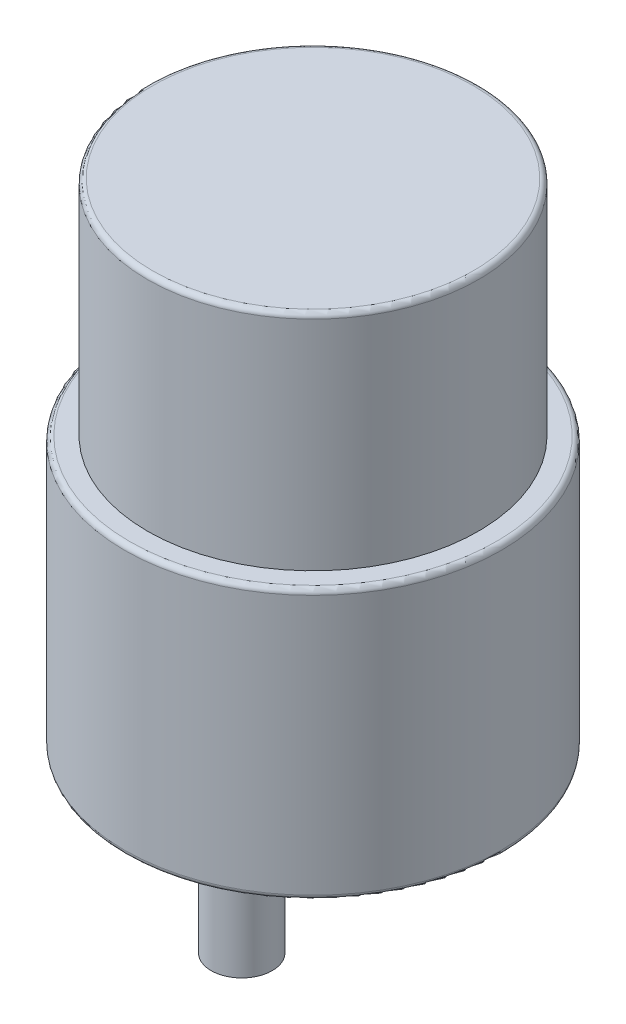
SolidWorks part; units mm, degrees
ref_plane "前视基准面" through (0, 0, 0) normal (0, 0, 1) x (1, 0, 0)
ref_plane "上视基准面" through (0, 0, 0) normal (0, 1, 0) x (1, 0, 0)
ref_plane "右视基准面" through (0, 0, 0) normal (1, 0, 0) x (0, 0, -1)
sketch "草图1" plane through (0, 0, 0) normal (0, 1, 0) x (1, 0, 0)
  circle A0 centre (0, 0) radius 18.5
  dimension "D1" = 37
extrude "凸台-拉伸1" add sketch "草图1" along normal blind 26.5
sketch "草图2" plane through (0, 26.5, 0) normal (0, 1, 0) x (1, 0, 0)
  circle A0 centre (0, 0) radius 16.25
  dimension "D1" = 32.5
extrude "凸台-拉伸2" add sketch "草图2" along normal blind 21.9
sketch "草图3" plane through (0, 0, 0) normal (0, -1, 0) x (1, 0, 0)
  line L0 (-18.5, 0) -> (18.5, 0) construction
  circle A0 centre (0, 0) radius 18.5 construction
  circle A1 centre (-7, 0) radius 6
  dimension "D1" = 12
  dimension "D2" = 7
extrude "凸台-拉伸3" add sketch "草图3" along normal blind 6
sketch "草图4" plane through (0, -6, 0) normal (0, -1, 0) x (1, 0, 0)
  circle A0 centre (-7, 0) radius 3
  dimension "D1" = 6
extrude "凸台-拉伸4" add sketch "草图4" along normal blind 15
sketch "草图5" plane through (0, -21, 0) normal (0, -1, 0) x (1, 0, 0)
  line L0 (-9.4, -1.8) -> (-9.4, 1.8)
  arc A0 (-9.4, 1.8) -> (-9.4, -1.8) centre (-7, 0) ccw
  dimension "D2" = 6
  dimension "D1" = 2.4
extrude "切除-拉伸1" cut sketch "草图5" against normal blind 12
fillet "圆角1" radius 0.5 3 edges at (0, 48.4, 16.25) (0, 26.5, 18.5) (0, 0, 18.5)
sketch "草图6" plane through (0, 0, 0) normal (0, -1, 0) x (1, 0, 0)
  circle A0 centre (0, 0) radius 15.5 construction
  circle A1 centre (0, -15.5) radius 1.5
  circle A2 centre (-13.4234, -7.75) radius 1.5
  circle A3 centre (-13.4234, 7.75) radius 1.5
  circle A4 centre (0, 15.5) radius 1.5
  circle A5 centre (13.4234, 7.75) radius 1.5
  circle A6 centre (13.4234, -7.75) radius 1.5
  point P17 (0, 0)
  dimension "D1" = 31
  dimension "D2" = 3
  dimension "D3" = 6
extrude "切除-拉伸2" cut sketch "草图6" against normal blind 3
